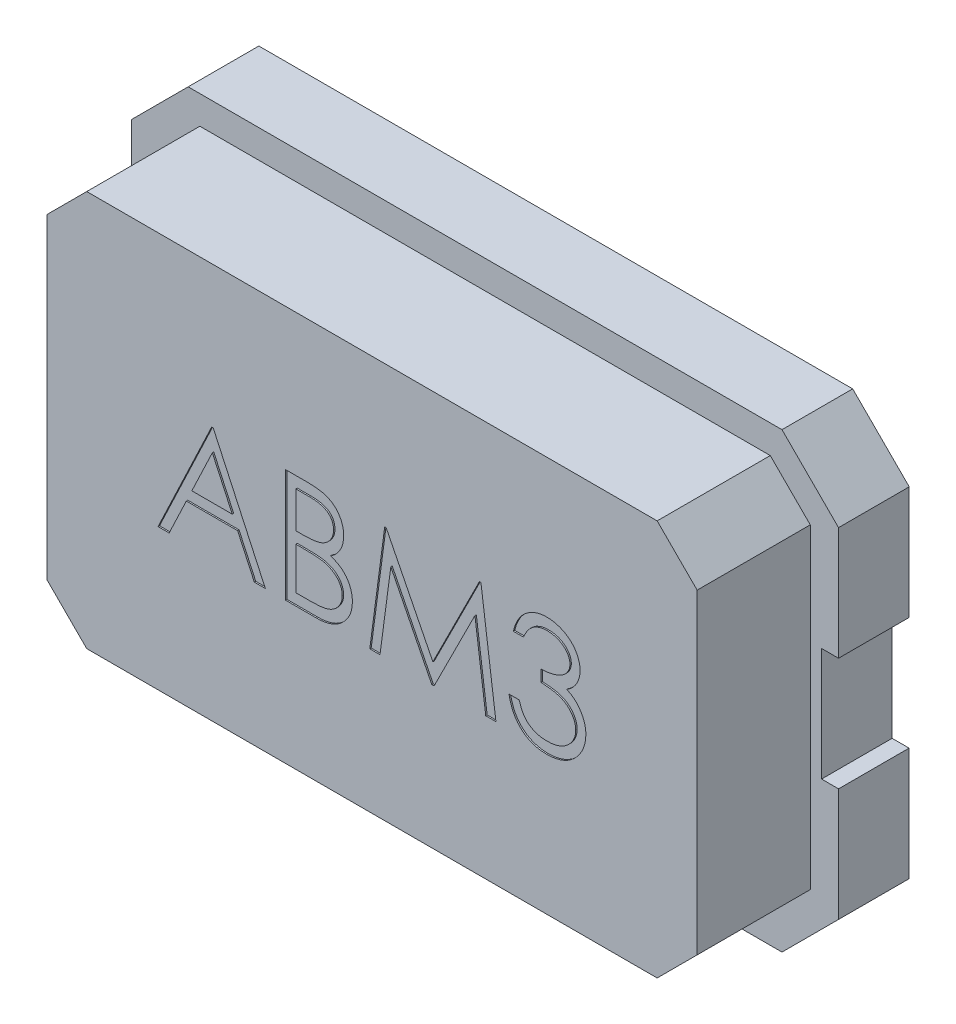
SolidWorks part; units mm, degrees
ref_plane "Plan de face" through (0, 0, 0) normal (0, 0, 1) x (1, 0, 0)
ref_plane "Plan de dessus" through (0, 0, 0) normal (0, 1, 0) x (1, 0, 0)
ref_plane "Plan de droite" through (0, 0, 0) normal (1, 0, 0) x (0, 0, -1)
sketch "Sketch1" plane through (0, 0, 0) normal (0, 0, 1) x (1, 0, 0)
  line L1 (-2.5, 1.6) -> (2.5, 1.6)
  line L2 (-2.5, 1.6) -> (-2.5, -1.6)
  line L3 (-2.5, -1.6) -> (2.5, -1.6)
  line L4 (2.5, 1.6) -> (2.5, -1.6)
  line L5 (-2.5, 1.6) -> (2.5, -1.6) construction
  line L6 (-2.5, -1.6) -> (2.5, 1.6) construction
  point P0 (0, 0)
  dimension "D1" = 3.2
  dimension "D2" = 5
extrude "Boss-Extrude1" add sketch "Sketch1" along normal blind 0.5
chamfer "Chamfer1" distance 0.4 angle 45 4 edges at (-2.5, 1.6, 0.25) (-2.5, -1.6, 0.25) (2.5, -1.6, 0.25) (2.5, 1.6, 0.25)
sketch "Sketch2" plane through (0, 0, 0.5) normal (0, 0, 1) x (1, 0, 0)
  line L16 (2.0172, 1.4) -> (-2.0172, 1.4)
  line L17 (-2.0172, 1.4) -> (-2.3, 1.1172)
  line L18 (-2.3, 1.1172) -> (-2.3, -1.1172)
  line L19 (-2.3, -1.1172) -> (-2.0172, -1.4)
  line L20 (-2.0172, -1.4) -> (2.0172, -1.4)
  line L21 (2.0172, -1.4) -> (2.3, -1.1172)
  line L22 (2.3, -1.1172) -> (2.3, 1.1172)
  line L23 (2.3, 1.1172) -> (2.0172, 1.4)
  line L24 (2.0172, 1.4) -> (-2.0172, 1.4)
  line L25 (-2.0172, 1.4) -> (-2.3, 1.1172)
  line L26 (-2.3, 1.1172) -> (-2.3, -1.1172)
  line L27 (-2.3, -1.1172) -> (-2.0172, -1.4)
  line L28 (-2.0172, -1.4) -> (2.0172, -1.4)
  line L29 (2.0172, -1.4) -> (2.3, -1.1172)
  line L30 (2.3, -1.1172) -> (2.3, 1.1172)
  line L31 (2.3, 1.1172) -> (2.0172, 1.4)
  dimension "D1" = 0.2
extrude "Boss-Extrude2" add sketch "Sketch2" along normal offset from surface (0.8 mm away) 1.3 up to face at (0, 0, 0)
sketch "Sketch3" plane through (0, 0, 1.3) normal (0, 0, 1) x (1, 0, 0)
  line L0 (-2.5696, -0.4) -> (2.5696, -0.4) construction
  line L1 (0, -0.4) -> (0, 0) construction
  text T0 "ABM3" font "Century Gothic" height 0.8
  point P6 (2.5696, -0.5157)
  dimension "D1" = 0.4
extrude "Cut-Extrude1" cut sketch "Sketch3" against normal blind 0.01
sketch "Sketch4" plane through (0, 0, 0.5) normal (0, 0, 1) x (1, 0, 0)
  line L0 (-2.38, 0) -> (0, 0) construction
  line L1 (-2.65, 0.4) -> (-2.38, 0.4)
  line L2 (-2.65, 0.4) -> (-2.65, -0.4)
  line L3 (-2.65, -0.4) -> (-2.38, -0.4)
  line L4 (-2.38, 0.4) -> (-2.38, -0.4)
  line L5 (-2.5, 1.2) -> (-2.5, -1.2) construction
  dimension "D1" = 0.8
  dimension "D2" = 0.12
extrude "Cut-Extrude2" cut sketch "Sketch4" against normal through all
sketch "Sketch6" plane through (0, 0, 0) normal (0, 0, -1) x (-1, 0, 0)
  line L0 (2.5, 1.2) -> (2.5, 0.4) construction
  line L1 (2.5, 1) -> (1.2, 1)
  line L2 (2.5, 1) -> (2.5, -1)
  line L3 (2.5, -1) -> (1.2, -1)
  line L4 (1.2, 1) -> (1.2, -1)
  line L5 (0, 0) -> (1.2, 0) construction
  dimension "D1" = 2
  dimension "D2" = 1.3
extrude "Cut-Extrude3" cut sketch "Sketch6" against normal blind 0.001
mirror "Mirror1" about plane through (0, 0, 0) normal (1, 0, 0) of "Cut-Extrude3", "Cut-Extrude2"
